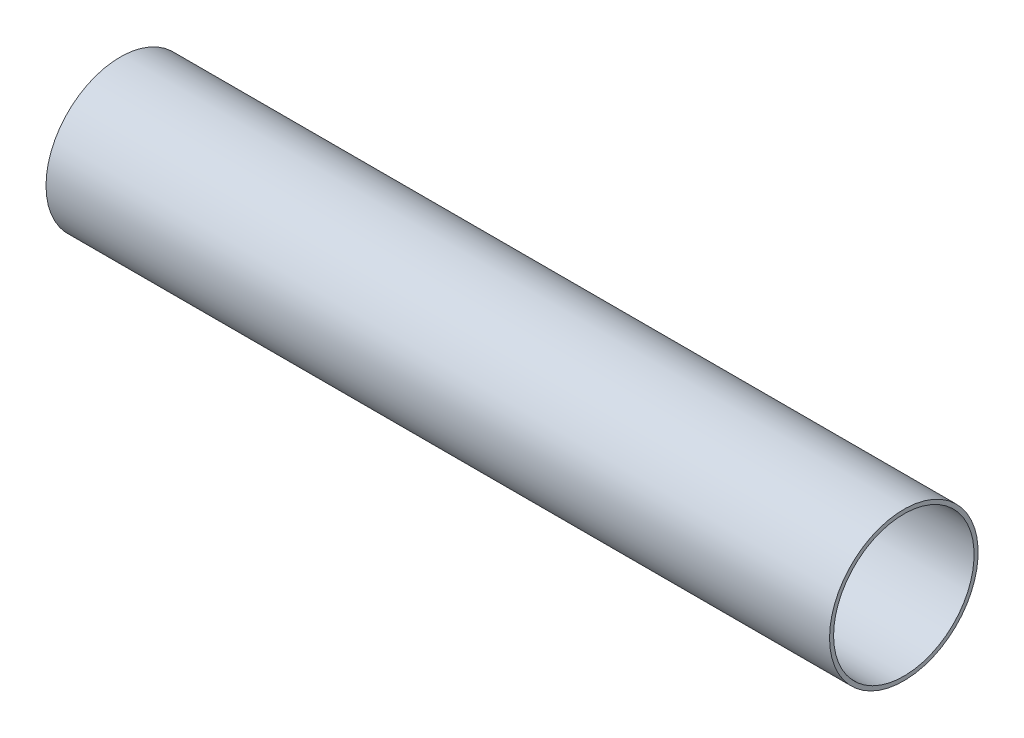
SolidWorks part; units mm, degrees
ref_plane "Front Plane" through (0, 0, 0) normal (0, 0, 1) x (1, 0, 0)
ref_plane "Top Plane" through (0, 0, 0) normal (0, 1, 0) x (1, 0, 0)
ref_plane "Right Plane" through (0, 0, 0) normal (1, 0, 0) x (0, 0, -1)
sketch "Sketch1" plane through (0, 0, 0) normal (1, 0, 0) x (0, 0, -1)
  circle A0 centre (0, 0) radius 27.3304
  circle A1 centre (0, 0) radius 28.9052
  dimension "D1" = 54.6608
  dimension "D2" = 57.8104
extrude "Boss-Extrude1" add sketch "Sketch1" along normal blind 304.8 contours A0 | A1 A0
